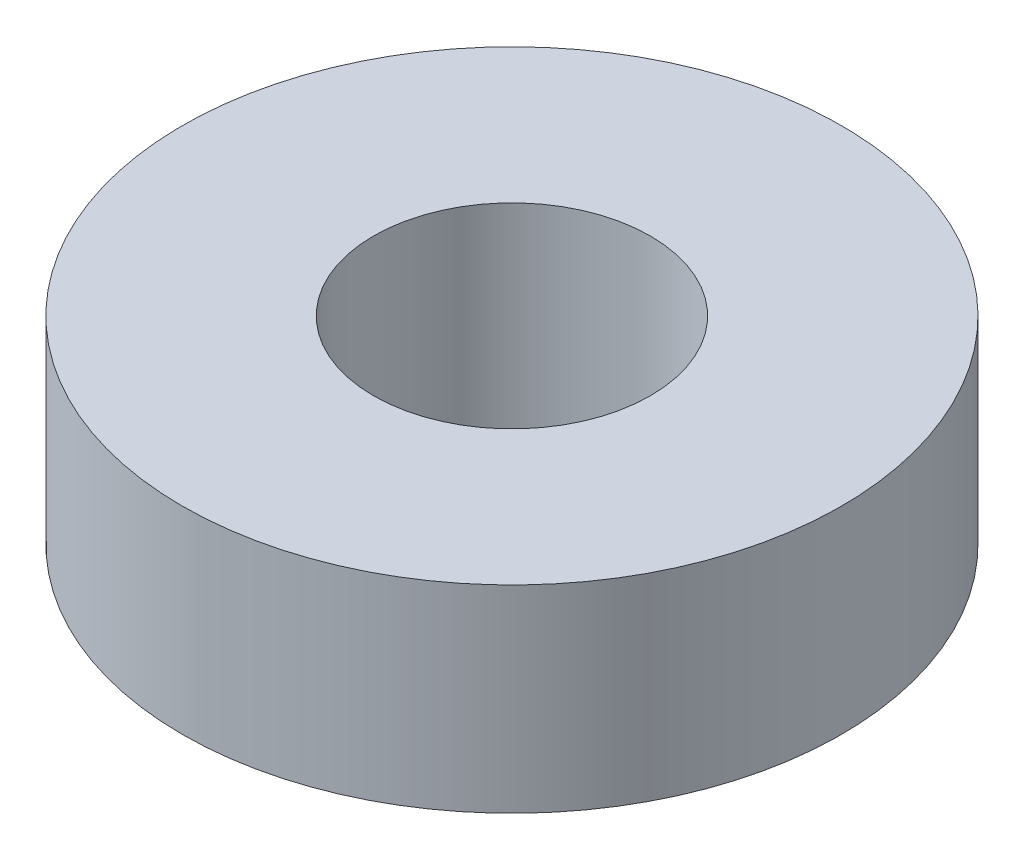
SolidWorks part; units mm, degrees
ref_plane "Front Plane" through (0, 0, 0) normal (0, 0, 1) x (1, 0, 0)
ref_plane "Top Plane" through (0, 0, 0) normal (0, 1, 0) x (1, 0, 0)
ref_plane "Right Plane" through (0, 0, 0) normal (1, 0, 0) x (0, 0, -1)
sketch "Sketch1" plane through (0, 0, 0) normal (0, 1, 0) x (1, 0, 0)
  circle A0 centre (0, 0) radius 2.1
  circle A1 centre (0, 0) radius 5
extrude "Boss-Extrude1" add sketch "Sketch1" along normal blind 3
